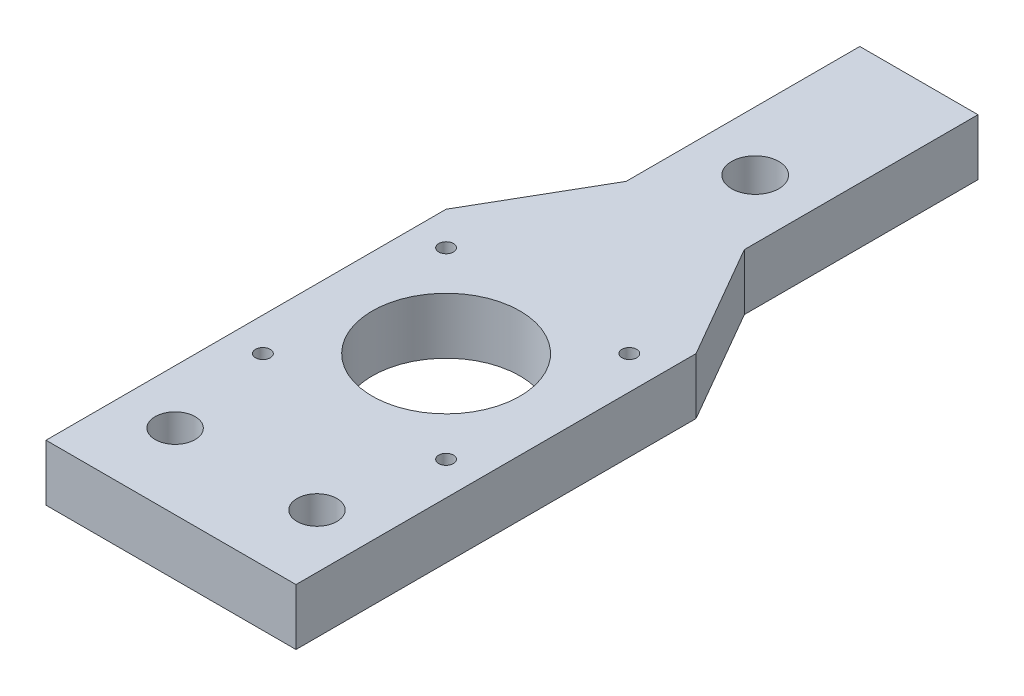
SolidWorks part; units mm, degrees
ref_plane "Front Plane" through (0, 0, 0) normal (0, 0, 1) x (1, 0, 0)
ref_plane "Top Plane" through (0, 0, 0) normal (0, 1, 0) x (1, 0, 0)
ref_plane "Right Plane" through (0, 0, 0) normal (1, 0, 0) x (0, 0, -1)
sketch "Sketch2" plane through (0, 0, 0) normal (0, 1, 0) x (1, 0, 0)
  line L0 (10, 0) -> (10, -100) construction
  line L1 (0, 0) -> (20, 0)
  line L2 (0, 0) -> (0, -100)
  line L3 (0, -100) -> (20, -100)
  line L4 (20, 0) -> (20, -100)
  line L5 (-11.15, -58.85) -> (0, -39.5376)
  line L6 (-11.15, -101.15) -> (31.15, -101.15)
  line L7 (-11.15, -101.15) -> (-11.15, -58.85)
  line L8 (-11.15, -58.85) -> (31.15, -58.85)
  line L9 (31.15, -101.15) -> (31.15, -58.85)
  line L10 (-11.15, -101.15) -> (31.15, -58.85) construction
  line L11 (-11.15, -58.85) -> (31.15, -101.15) construction
  line L12 (20, -39.5376) -> (31.15, -58.85)
  circle A0 centre (10, -80) radius 12.5
  circle A1 centre (10, -27.7) radius 4
  point P17 (0, -36.2081)
  dimension "D3" = 8
  dimension "D4" = 25
  dimension "D1" = 100
  dimension "D2" = 20
  dimension "D5" = 52.3
  dimension "D6" = 20
  dimension "D7" = 42.3
  dimension "D8" = 42.3
  dimension "D9" = 60
  dimension "D10" = 60
extrude "Boss-Extrude1" add sketch "Sketch2" along normal blind 9.525 contours L2 L8 L4 L1 A1 | L5 L8 L2 | L12 L4 L8 | A0 L4 L3 L2 L8 L7 L6 L9 | A0 L4 L8 L2 | A0 L2 L3 L4
sketch "Sketch3" plane through (0, 9.525, 0) normal (0, 1, 0) x (1, 0, 0)
  line L1 (-5.5, -95.5) -> (25.5, -95.5) construction
  line L2 (-5.5, -95.5) -> (-5.5, -64.5) construction
  line L3 (-5.5, -64.5) -> (25.5, -64.5) construction
  line L4 (25.5, -95.5) -> (25.5, -64.5) construction
  line L5 (-5.5, -95.5) -> (25.5, -64.5) construction
  line L6 (-5.5, -64.5) -> (25.5, -95.5) construction
  point P0 (10, -80)
  dimension "D1" = 31
hole_wizard "Tap Drill for M3x0.5 Tap1" positions "Sketch4" profile "Sketch5" hole size "M3x0.5" standard "ANSI Metric" end condition through all
sketch "Sketch4" plane through (0, 9.525, 0) normal (0, 1, 0) x (1, 0, 0)
  point P0 (-5.5, -64.5)
  point P3 (25.5, -64.5)
  point P6 (25.5, -95.5)
  point P9 (-5.5, -95.5)
sketch "Sketch5" plane through (-5.5, 9.525, 64.5) normal (1, 0, 0) x (0, 0, 1)
  line L0 (0, 0) -> (0, 9.525)
  line L1 (0, 9.525) -> (1.25, 9.525)
  line L2 (1.25, 9.525) -> (1.25, 0)
  line L5 (1.25, 0) -> (0, 0)
  line L11 (0, -6.35) -> (0, 107.95) construction
  dimension "Thru Hole Dia." = 2.5
  dimension "Thru Hole Depth" = 9.525
sketch "Sketch7" plane through (0, 9.525, 0) normal (0, 1, 0) x (1, 0, 0)
  line L0 (-11.15, -101.15) -> (31.15, -101.15) construction
  line L1 (-11.15, -101.15) -> (31.15, -101.15)
  line L2 (-11.15, -101.15) -> (-11.15, -126.55)
  line L3 (-11.15, -126.55) -> (31.15, -126.55)
  line L4 (31.15, -101.15) -> (31.15, -126.55)
  point P4 (19.2957, -101.15)
  dimension "D1" = 25.4
extrude "Boss-Extrude2" add sketch "Sketch7" against normal up to surface (9.525 mm away) up to face at (-5.5, 0, 65.75)
sketch "Sketch8" plane through (0, 9.525, 0) normal (0, 1, 0) x (1, 0, 0)
  line L0 (10, -126.55) -> (10, -113.85) construction
  line L1 (-11.15, -126.55) -> (31.15, -126.55) construction
  line L2 (-2, -113.85) -> (22, -113.85) construction
  point P7 (10, -113.85)
  dimension "D1" = 12.7
  dimension "D2" = 24
hole_wizard "1/4 Clearance Hole1" positions "Sketch9" profile "Sketch10" hole size "1/4" standard "ANSI Inch" end condition through all
sketch "Sketch9" plane through (0, 9.525, 0) normal (0, 1, 0) x (1, 0, 0)
  point P0 (-2, -113.85)
  point P3 (22, -113.85)
sketch "Sketch10" plane through (-2, 9.525, 113.85) normal (1, 0, 0) x (0, 0, 1)
  line L0 (0, 0) -> (0, 9.525)
  line L1 (0, 9.525) -> (3.3782, 9.525)
  line L2 (3.3782, 9.525) -> (3.3782, 0)
  line L5 (3.3782, 0) -> (0, 0)
  line L11 (0, -6.35) -> (0, 107.95) construction
  dimension "Thru Hole Dia." = 6.7564
  dimension "Thru Hole Depth" = 9.525
